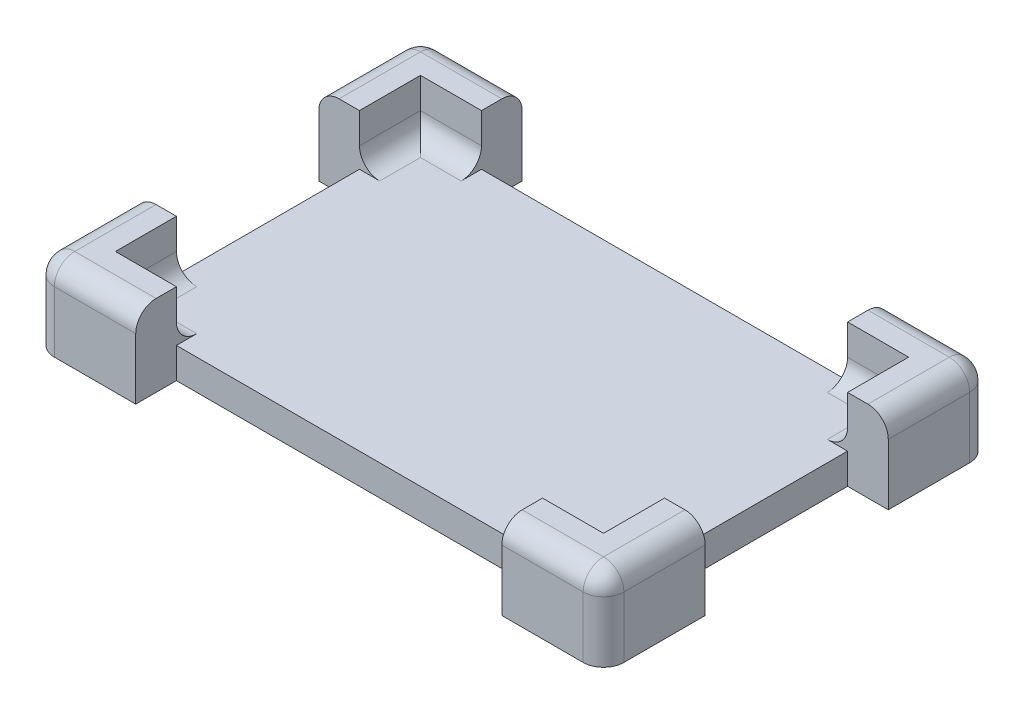
SolidWorks part; units mm, degrees
ref_plane "Front Plane" through (0, 0, 0) normal (0, 0, 1) x (1, 0, 0)
ref_plane "Top Plane" through (0, 0, 0) normal (0, 1, 0) x (1, 0, 0)
ref_plane "Right Plane" through (0, 0, 0) normal (1, 0, 0) x (0, 0, -1)
sketch "Sketch1" plane through (0, 0, 0) normal (0, 1, 0) x (1, 0, 0)
  line L0 (-12, 7.5) -> (12, 7.5)
  line L1 (-11, -6.5) -> (11, -6.5) construction
  line L2 (-11, -6.5) -> (-11, 6.5) construction
  line L3 (-11, 6.5) -> (11, 6.5) construction
  line L4 (11, -6.5) -> (11, 6.5) construction
  line L5 (-11, -6.5) -> (11, 6.5) construction
  line L6 (-11, 6.5) -> (11, -6.5) construction
  line L7 (12, -7.5) -> (12, 7.5)
  line L8 (-12, -7.5) -> (12, -7.5)
  line L9 (-12, -7.5) -> (-12, 7.5)
  point P0 (0, 0)
  point P10 (0, 0)
  point P16 (0, 0)
  dimension "D1" = 13
  dimension "D2" = 22
  dimension "D3" = 1
extrude "Boss-Extrude1" add sketch "Sketch1" along normal mid plane 1.5
sketch "Sketch2" plane through (0, 0.75, 0) normal (0, 1, 0) x (1, 0, 0)
  line L0 (-12, 4.5) -> (-14, 4.5)
  line L1 (-12, 7.5) -> (-12, -7.5) construction
  line L2 (-14, 4.5) -> (-14, 9.5)
  line L3 (-14, 9.5) -> (-9, 9.5)
  line L4 (-9, 9.5) -> (-9, 7.5)
  line L5 (12, 7.5) -> (-12, 7.5) construction
  line L6 (-9, 7.5) -> (-12, 7.5)
  line L7 (-12, 7.5) -> (-12, 4.5)
  dimension "D1" = 3
  dimension "D2" = 2
extrude "Boss-Extrude2" add sketch "Sketch2" along normal blind 2.5 and the other way blind 1.5
mirror "Mirror1" about plane through (0, 0, 0) normal (1, 0, 0) of "Boss-Extrude2"
mirror "Mirror2" about plane through (0, 0, 0) normal (0, 0, 1) of "Mirror1", "Boss-Extrude2"
fillet "Fillet1" radius 1 20 edges at (-14, 1.25, 9.5) (-14, 3.25, 7) (-11.5, 3.25, 9.5) (14, 1.25, 9.5) (11.5, 3.25, 9.5) (14, 3.25, 7) (14, 1.25, -9.5) (14, 3.25, -7) (11.5, 3.25, -9.5) (-11.5, 3.25, -9.5) (-14, 3.25, -7) (-14, 1.25, -9.5) (-10.5, 0.75, -7.5) (-12, 0.75, -6) (10.5, 0.75, -7.5) (12, 0.75, -6) (12, 0.75, 6) (10.5, 0.75, 7.5) (-10.5, 0.75, 7.5) (-12, 0.75, 6)
